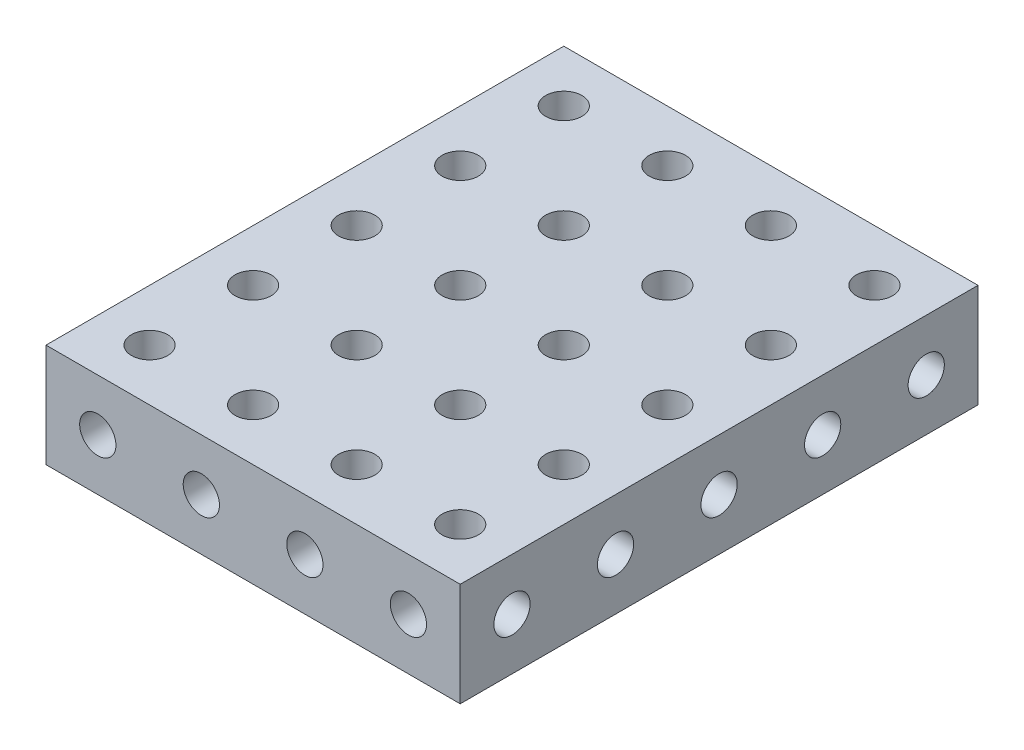
SolidWorks part; units mm, degrees
ref_plane "Plan de face" through (0, 0, 0) normal (0, 0, 1) x (1, 0, 0)
ref_plane "Plan de dessus" through (0, 0, 0) normal (0, 1, 0) x (1, 0, 0)
ref_plane "Plan de droite" through (0, 0, 0) normal (1, 0, 0) x (0, 0, -1)
sketch "Esquisse1" plane through (0, 0, 0) normal (1, 0, 0) x (0, 0, -1)
  line L1 (0, 0) -> (50, 0)
  line L2 (0, 0) -> (0, 10)
  line L3 (0, 10) -> (50, 10)
  line L4 (50, 0) -> (50, 10)
  dimension "D1" = 50
  dimension "D2" = 10
extrude "Boss.-Extru.1" add sketch "Esquisse1" along normal blind 40
sketch "Esquisse2" plane through (0, 10, 0) normal (0, 1, 0) x (1, 0, 0)
  line L0 (0, 45) -> (40, 45) construction
  line L4 (40, 50) -> (0, 50) construction
  circle A0 centre (5, 45) radius 1.75
  circle A1 centre (15, 45) radius 1.75
  circle A2 centre (25, 45) radius 1.75
  circle A3 centre (35, 45) radius 1.75
  circle A4 centre (5, 35) radius 1.75
  circle A5 centre (15, 35) radius 1.75
  circle A6 centre (25, 35) radius 1.75
  circle A7 centre (35, 35) radius 1.75
  circle A8 centre (5, 25) radius 1.75
  circle A9 centre (15, 25) radius 1.75
  circle A10 centre (25, 25) radius 1.75
  circle A11 centre (35, 25) radius 1.75
  circle A12 centre (5, 15) radius 1.75
  circle A13 centre (15, 15) radius 1.75
  circle A14 centre (25, 15) radius 1.75
  circle A15 centre (35, 15) radius 1.75
  circle A16 centre (5, 5) radius 1.75
  circle A17 centre (15, 5) radius 1.75
  circle A18 centre (25, 5) radius 1.75
  circle A19 centre (35, 5) radius 1.75
  dimension "D4" = 3.5
  dimension "D1" = 5
  dimension "D2" = 10
  dimension "D3" = 10
  dimension "D5" = 10
  dimension "D6" = 5
  dimension "D7" = 5
extrude "Enlèv. mat.-Extru.1" cut sketch "Esquisse2" against normal through all
sketch "Esquisse3" plane through (0, 0, 0) normal (0, 0, 1) x (1, 0, 0)
  line L0 (0, 5) -> (40, 5) construction
  line L1 (0, 10) -> (0, 0) construction
  line L2 (40, 10) -> (40, 0) construction
  circle A0 centre (5, 5) radius 1.75
  circle A1 centre (15, 5) radius 1.75
  circle A2 centre (25, 5) radius 1.75
  circle A3 centre (35, 5) radius 1.75
  dimension "D4" = 3.5
  dimension "D1" = 5
  dimension "D2" = 10
  dimension "D3" = 10
  dimension "D5" = 10
extrude "Enlèv. mat.-Extru.2" cut sketch "Esquisse3" against normal through all
sketch "Esquisse4" plane through (40, 0, 0) normal (1, 0, 0) x (0, 0, -1)
  line L0 (0, 5) -> (50, 5) construction
  line L1 (0, 10) -> (0, 0) construction
  line L2 (50, 0) -> (50, 10) construction
  circle A0 centre (5, 5) radius 1.75
  circle A1 centre (15, 5) radius 1.75
  circle A2 centre (25, 5) radius 1.75
  circle A3 centre (35, 5) radius 1.75
  circle A4 centre (45, 5) radius 1.75
  dimension "D1" = 3.5
  dimension "D2" = 5
  dimension "D3" = 5
extrude "Enlèv. mat.-Extru.3" cut sketch "Esquisse4" against normal blind 40
